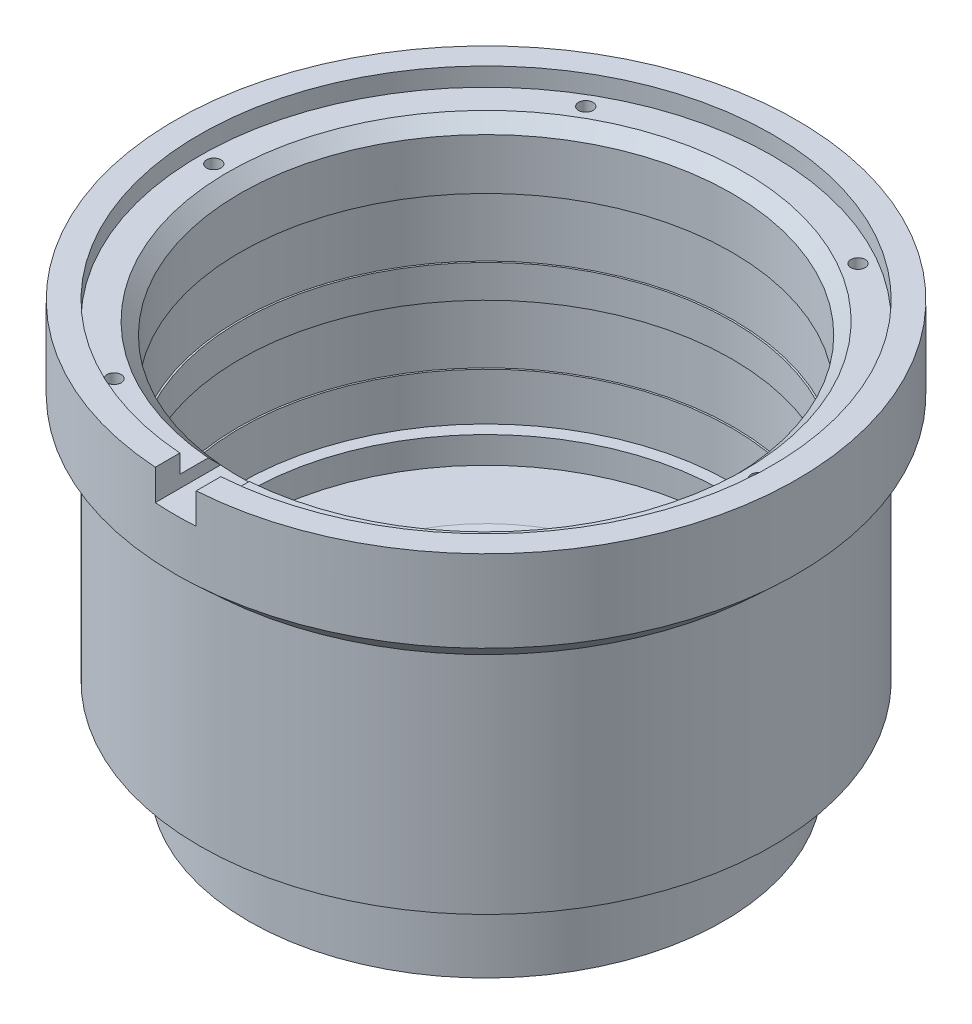
SolidWorks part; units mm, degrees
material "1060 Alloy"
ref_plane "Front Plane" through (0, 0, 0) normal (0, 0, 1) x (1, 0, 0)
ref_plane "Top Plane" through (0, 0, 0) normal (0, 1, 0) x (1, 0, 0)
ref_plane "Right Plane" through (0, 0, 0) normal (1, 0, 0) x (0, 0, -1)
sketch "Sketch7" plane through (0, 0, 0) normal (0, 0, 1) x (1, 0, 0)
  line L0 (0, -30.2319) -> (0, 30.2319) construction
  line L1 (-38, 38.06) -> (-35, 38.06)
  line L2 (-35, 38.06) -> (-35, 35.81)
  line L3 (-35, 35.81) -> (-30.0375, 35.81)
  line L7 (-9, 0) -> (-29.075, 0)
  line L10 (-38, 3.255) -> (-38, 38.06)
  line L13 (-30.0375, 35.81) -> (-30.0375, 3.255)
  line L14 (-30.0375, 3.255) -> (-29.075, 3.255)
  line L15 (-29.075, 3.255) -> (-29.075, 0)
  line L16 (-9, 0) -> (-9, -2.94)
  line L17 (-12, -13.19) -> (-38, -13.19)
  line L18 (-38, -13.19) -> (-38, 3.255)
  line L19 (-9, -2.94) -> (-12, -2.94)
  line L20 (-12, -2.94) -> (-12, -13.19)
  point P4 (0, 0)
  point P20 (-32.5187, 35.81)
  dimension "D2" = 2.25
  dimension "D3" = 4.9625
  dimension "D5" = 35.81
  dimension "D4" = 30.0375
  dimension "D8" = 32.555
  dimension "D10" = 0.9625
  dimension "D12" = 38
  dimension "D13" = 51.25
  dimension "D9" = 12
  dimension "D14" = 9
  dimension "D6" = 10.25
revolve "Base Motor Housing" add sketch "Sketch7" angle 360 about L0
chamfer "Top Chamfer" distance 1.5 angle 45 1 edges at (0, 35.81, -30.0375)
chamfer "Back Chamfer" distance 2 angle 80 1 edges at (0, 0, -9)
ref_plane "Chamfer plane" through (0, 34.31, 0) normal (0, -1, 0) x (-1, 0, 0)
sketch "Sketch8" plane through (0, 38.06, 0) normal (0, 1, 0) x (1, 0, 0)
  line L0 (0, 0) -> (0, -38) construction
  line L1 (-2.5, -38) -> (2.5, -38)
  line L2 (-2.5, -38) -> (-2.5, -29.9333)
  line L3 (-2.5, -29.9333) -> (2.5, -29.9333)
  line L4 (2.5, -38) -> (2.5, -29.9333)
  circle A0 centre (0, 0) radius 38 construction
  circle A2 centre (0, 0) radius 30.0375 construction
  point P10 (0, -38)
  dimension "D1" = 5
extrude "Wire Hole" cut sketch "Sketch8" against normal up to surface (3.75 mm away)
sketch "Sketch9" plane through (0, 35.81, 0) normal (0, 1, 0) x (1, 0, 0)
  line L0 (-31.5375, 0) -> (-35, 0) construction
  line L1 (-2.5, -34.9106) -> (-2.5, -31.4383) construction
  line L2 (-2.5, -29.9333) -> (-2.5, -37.9177) construction
  circle A2 centre (0, 0) radius 33.2688 construction
  circle A3 centre (-33.2688, 0) radius 0.875
  circle A4 centre (-16.6344, 28.8116) radius 0.875
  circle A5 centre (16.6344, 28.8116) radius 0.875
  circle A6 centre (33.2688, 0) radius 0.875
  circle A7 centre (16.6344, -28.8116) radius 0.875
  circle A8 centre (-16.6344, -28.8116) radius 0.875
  arc A9 (2.5, -34.9106) -> (-2.5, -34.9106) centre (0, 0) ccw construction
  arc A10 (2.5, -34.9106) -> (-2.5, -34.9106) centre (0, 0) ccw construction
  arc A11 (2.5, -31.4383) -> (-2.5, -31.4383) centre (0, 0) ccw construction
  arc A14 (2.5, -31.4383) -> (-2.5, -31.4383) centre (0, 0) ccw construction
  point P21 (0, 0)
  point P31 (-33.2688, 0)
  dimension "D2" = 1.75
  dimension "D3" = 6
extrude "Front-Holes" cut sketch "Sketch9" against normal blind 6
sketch "Sketch10" plane through (0, -13.19, 0) normal (0, -1, 0) x (1, 0, 0)
  line L0 (-12, 0) -> (-38, 0) construction
  circle A2 centre (0, 0) radius 12 construction
  circle A3 centre (0, 0) radius 38 construction
  circle A4 centre (-25, 0) radius 1.375
  circle A5 centre (-12.5, 21.6506) radius 1.375
  circle A6 centre (12.5, 21.6506) radius 1.375
  circle A7 centre (25, 0) radius 1.375
  circle A8 centre (12.5, -21.6506) radius 1.375
  circle A9 centre (-12.5, -21.6506) radius 1.375
  circle A10 centre (0, 0) radius 25 construction
  circle A13 centre (0, 0) radius 38 construction
  point P22 (0, 0)
  dimension "D1" = 2.75
  dimension "D2" = 6
extrude "Back-Holes" cut sketch "Sketch10" against normal blind 5
sketch "Sketch11" plane through (0, 0, 0) normal (0, 0, 1) x (1, 0, 0)
  line L0 (29, -13.19) -> (29, -5.69)
  line L3 (38, -13.19) -> (38, 38.06) construction
  line L4 (38, 28.06) -> (38, -13.19)
  line L5 (38, -13.19) -> (29, -13.19)
  line L6 (0, -8.19) -> (26.375, -8.19) construction
  line L7 (26.375, -8.19) -> (26.375, 38.06) construction
  line L8 (35, 38.06) -> (-35, 38.06) construction
  line L9 (29, -5.69) -> (38, -5.69) construction
  line L10 (0, 0) -> (0, -13.4206) construction
  line L11 (29, -5.69) -> (35, -2.2259)
  line L12 (35, -2.2259) -> (35, 25.2741)
  line L13 (35, 25.2741) -> (38, 28.06)
  line L14 (35, 25.2741) -> (37.9362, 25.2741) construction
  line L15 (-38, -13.19) -> (38, -13.19) construction
  line L19 (30.0375, 3.255) -> (-30.0375, 3.255) construction
  line L23 (30.0375, 3.255) -> (-30.0375, 3.255) construction
  dimension "D3" = 7.5
  dimension "D2" = 30
  dimension "D1" = 35
  dimension "D5" = 29
  dimension "D6" = 27.5
  dimension "D4" = 10
revolve "Lightening Cut" cut sketch "Sketch11" angle 360 about L10
sketch "Sketch12" plane through (0, 0, 0) normal (0, 0, 1) x (1, 0, 0)
  line L0 (-30.0375, 3.255) -> (-30.7875, 3.255)
  line L1 (30.0375, 3.255) -> (-30.0375, 3.255) construction
  line L2 (-30.7875, 3.255) -> (-30.0375, 3.688)
  line L3 (-30.0375, 3.688) -> (-30.0375, 3.255)
  line L4 (0, -4.2819) -> (0, 6.8752) construction
  line L5 (30.0375, 3.255) -> (-30.0375, 3.255) construction
  dimension "D1" = 0.75
  dimension "D2" = 30
revolve "Undercut for Stator" cut sketch "Sketch12" angle 360 about L4
thread "Thread1" [suppressed] pitch 0.4 start angle 0, offset 0, length 0, pitch 0.4, diameter 1.75
ref_plane "Plane1" through (-34.1438, 35.81, 0) normal (0, 0, 1) x (-1, 0, 0)
sketch "Thread Profile1" plane through (-34.1438, 35.81, 0) normal (0, 0, 1) x (-1, 0, 0)
  line L0 (0, 0) -> (0, 0.4) construction
  line L1 (0, 0) -> (0.2165, 0.125)
  line L2 (0.2165, 0.125) -> (0.2165, 0.175)
  line L3 (0.2165, 0.175) -> (0, 0.3)
  line L4 (0.2165, 0.15) -> (0, 0.15) construction
  line L11 (0, 0) -> (0, 0.3)
  point P2 (0, 0)
  dimension "Pitch" = 0.4
  dimension "Profile_Angle" = 60
  dimension "Profile_Land" = 0.05
  dimension "Profile_Height" = 0.2165
thread "Thread2" [suppressed] pitch 0.5 start angle 0, offset 0, length 0, pitch 0.5, diameter 2.75
ref_plane "Plane3" through (-23.625, -13.19, 0) normal (0, 0, 1) x (1, 0, 0)
sketch "Thread Profile3" plane through (-23.625, -13.19, 0) normal (0, 0, 1) x (1, 0, 0)
  line L0 (0, 0) -> (0, 0.5) construction
  line L1 (0, 0) -> (0.2706, 0.1562)
  line L2 (0.2706, 0.1562) -> (0.2706, 0.2187)
  line L3 (0.2706, 0.2187) -> (0, 0.375)
  line L4 (0.2706, 0.1875) -> (0, 0.1875) construction
  line L11 (0, 0) -> (0, 0.375)
  point P2 (0, 0)
  dimension "Pitch" = 0.5
  dimension "Profile_Angle" = 60
  dimension "Profile_Land" = 0.0625
  dimension "Profile_Height" = 0.2706
pattern_circular "CirPattern1" [suppressed] count 6 over 360
ref_plane "Plane4" through (0, 18.7825, 0) normal (0, -1, 0) x (-1, 0, 0)
sketch "Sketch14" plane through (0, 0, 0) normal (0, 0, 1) x (1, 0, 0)
  line L0 (-30.0375, 28.0847) -> (-30.2475, 28.0847)
  line L2 (0, -10.4986) -> (0, 5.9571) construction
  line L3 (-30.2475, 28.0847) -> (-30.2475, 20.7825)
  line L4 (-30.2475, 20.7825) -> (-30.0375, 20.7825)
  line L5 (-30.0375, 28.0847) -> (-30.0375, 20.7825)
  line L6 (-33.8663, 18.7825) -> (33.8663, 18.7825) construction
  line L7 (-30.0375, 9.4803) -> (-30.2475, 9.4803)
  line L8 (-30.2475, 16.7825) -> (-30.0375, 16.7825)
  line L9 (-30.2475, 9.4803) -> (-30.2475, 16.7825)
  line L10 (-30.0375, 9.4803) -> (-30.0375, 16.7825)
  dimension "D1" = 30.0375
  dimension "D2" = 0.21
  dimension "D3" = 2
  dimension "D4" = 7.3022
revolve "Adhesive Trench" cut sketch "Sketch14" angle 360 about L2
equation "\"D2@Sketch9\"=\"Back_mount_hole\""
equation "\"Stator_OD\"= 60'No Tolerance given"
equation "\"A\"=35.81 'taken off spec sheet for 06808 (A)"
equation "\"Rotor_ID\"= 30'No Tolerance Given"
equation "\"back_bearing_Thickness\"= 5'-0.12"
equation "\"back_bearing_OD\"= 24'-0.009 https://www.mcmaster.com/5972K155/"
equation "\"D5@Sketch7\"=\"A\""
equation "\"Stator_Gap\"= 0.0375'+- 0.0125 (From 1.3.3.1 Kollmorgen manual)"
equation "\"Back_mount_hole\"= 1.75'To be tapped to M2 (USE LOCKTITE)"
equation "\"D1@Back-Holes\" = \"back_bearing_Thickness\""
equation "\"facePlate_Mount_Hole\"= 2.75'To be tapped to M3"
equation "\"D1@Sketch10\"=\"facePlate_Mount_Hole\""
equation "\"final_shaftD\"= 12'To fit in harmonic"
equation "\"back_bearing_ID\"= 15'"
equation "\"final_shaftL\"= 5.25+3+\"sheet_thick\"+\"connector_thick\"-3+\"harmon_coupleL\"+0.5-\"shaft_Ladjust\"'length to make everything nice and aligned"
equation "\"back_bearing_IDOD\"= 16.5'measured off CAD, actually 16.75, but rounded down to nicer number"
equation "\"rotor_shaftD\"= \"Rotor_ID\" - (\"rotor-shaft_gap\")*2'"
equation "\"front_bearing_ID\"= 12'https://www.mcmaster.com/5972K154/"
equation "\"front_bearing_OD\"= 21'-0.009"
equation "\"front_bearing_IDOD\"= 13.5'Measured off CAD. Actually 13.75, but rounded down"
equation "\"front_bearing_Thickness\"= 5'-0.12"
equation "\"rotor_thickness\"= 2.4'measured off CAD"
equation "\"rotor_height\"= 32.86'+-0.075 taken off spec sheet for 06826 (C)"
equation "\"D4@Sketch7\"=\"Stator_OD\"/2+\"Stator_Gap\""
equation "\"B\"= 26.3'+-0.35 taken off spec sheet for 06826"
equation "\"D8@Sketch7\"=(\"A\"-\"B\")/2+\"B\"+1.5"
equation "\"D3@Sketch11\"=\"back_bearing_Thickness\"*1.5"
equation "\"rotor-shaft_gap\" = 0.0185 '+-0.0065 (from manual)"
equation "\"D9@Sketch7\"=\"back_bearing_OD\"/2"
equation "\"D14@Sketch7\"=\"back_bearing_OD\"/2-3"
equation "\"D6@Sketch7\"= \"back_bearing_Thickness\" + 5.25"
equation "\"D3@Sketch7\"=5-\"Stator_Gap\""
equation "\"D10@Sketch7\"=1-\"Stator_Gap\""
equation "\"D1@Sketch14\"=\"Stator_OD\"/2+\"Stator_Gap\""
equation "\"D4@Sketch14\"=\"rotor_height\"/4.5"
equation "\"key_L\"= 20'-0.2 https://www.mcmaster.com/2977N19/"
equation "\"key_H\"= 4'-0.03"
equation "\"key_W\"= 4'-0.03"
equation "\"harmon_keyH\"= 13.8'+0.1 from drawing"
equation "\"harmon_coupleL\"= 21.5' taken from drawing https://www.harmonicdrive.net/_hd/content/caddownloads/dxf/csg-2uh-lw_gearheads/csg-20-100-2uh-lw.pdf"
equation "\"harmon_diam\"= 93' from drawing"
equation "\"harmon_BCD\"= 82' from drawing"
equation "\"harmon_holeD1\"= 5.5' from drawing"
equation "\"harmon_holeD2\"= 5' from drawing"
equation "\"harmon_holeAng\"= 22.5' from drawing"
equation "\"sheet_thick\"= 1/8*25.4 'random, replace w actual sheet thickness when u feel like :)"
equation "\"nut-thickness\"= 5 'idk measure the ones in the shop and adjust"
equation "\"connector_thick\"= 10' random for now"
equation "\"shaft_Ladjust\"= 6.5' sorry. It's silly, but it works."
